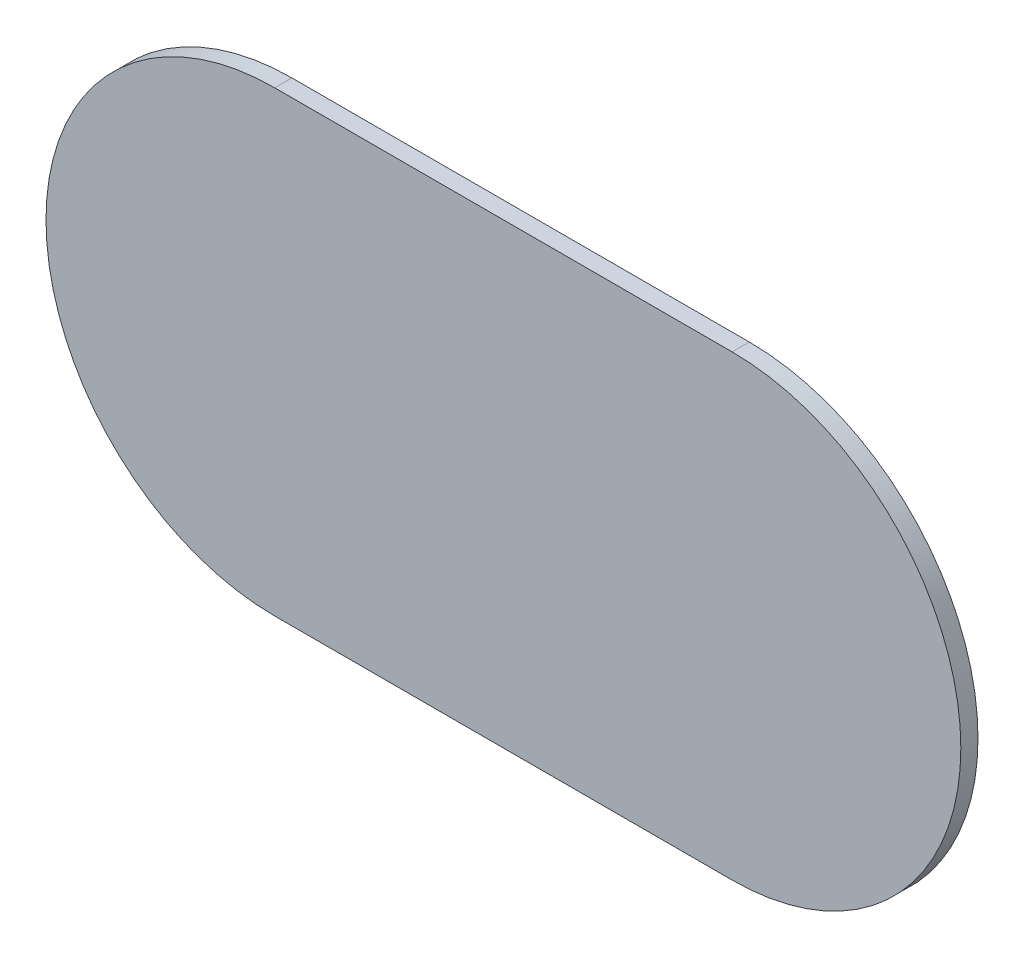
SolidWorks part; units mm, degrees
ref_plane "Спереди" through (0, 0, 0) normal (0, 0, 1) x (1, 0, 0)
ref_plane "Сверху" through (0, 0, 0) normal (0, 1, 0) x (1, 0, 0)
ref_plane "Справа" through (0, 0, 0) normal (1, 0, 0) x (0, 0, -1)
other "Configuration Table"
sketch "Эскиз1" plane through (0, 0, 0) normal (0, 0, 1) x (1, 0, 0)
  line L0 (-40, 0) -> (40, 0) construction
  line L2 (-40, 40) -> (40, 40)
  line L3 (-40, -40) -> (40, -40)
  arc A0 (-40, 40) -> (-40, -40) centre (-40, 0) ccw
  arc A1 (40, -40) -> (40, 40) centre (40, 0) ccw
  point P5 (0, 0)
  dimension "D1" = 80
  dimension "D2" = 160
extrude "Бобышка-Вытянуть1" add sketch "Эскиз1" along normal blind 3 contours L2 A1 L3 A0
